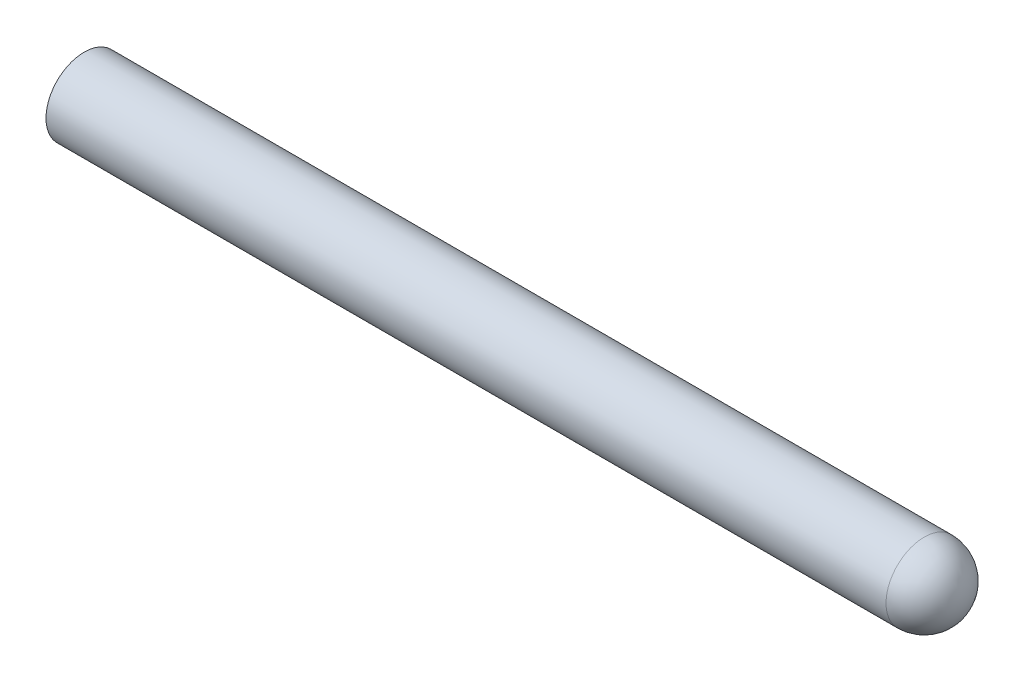
SolidWorks part; units mm, degrees
ref_plane "Front Plane" through (0, 0, 0) normal (0, 0, 1) x (1, 0, 0)
ref_plane "Top Plane" through (0, 0, 0) normal (0, 1, 0) x (1, 0, 0)
ref_plane "Right Plane" through (0, 0, 0) normal (1, 0, 0) x (0, 0, -1)
sketch "Sketch1" plane through (0, 0, 0) normal (1, 0, 0) x (0, 0, -1)
  circle A0 centre (0, 0) radius 12.7
  circle A1 centre (0, 0) radius 19.05
  dimension "D1" = 25.4
  dimension "D2" = 38.1
extrude "Boss-Extrude1" add sketch "Sketch1" along normal blind 355.6
sketch "Sketch3" plane through (0, 0, 0) normal (0, 0, 1) x (1, 0, 0)
  line L0 (355.6, -19.05) -> (355.6, 19.05) construction
  line L1 (355.6, 19.05) -> (355.6, 0)
  line L2 (355.6, 0) -> (374.65, 0)
  arc A0 (355.6, 19.05) -> (374.65, 0) centre (355.6, 0) cw
revolve "Revolve1" add sketch "Sketch3" angle 360 about L2
sketch "Sketch4" plane through (0, 0, 0) normal (-1, 0, 0) x (0, 0, 1)
  circle A0 centre (0, 0) radius 19.05 construction
  circle A1 centre (0, 0) radius 19.05
  circle A2 centre (0, 0) radius 9.525
  dimension "D1" = 19.05
extrude "Boss-Extrude2" add sketch "Sketch4" along normal blind 63.5
